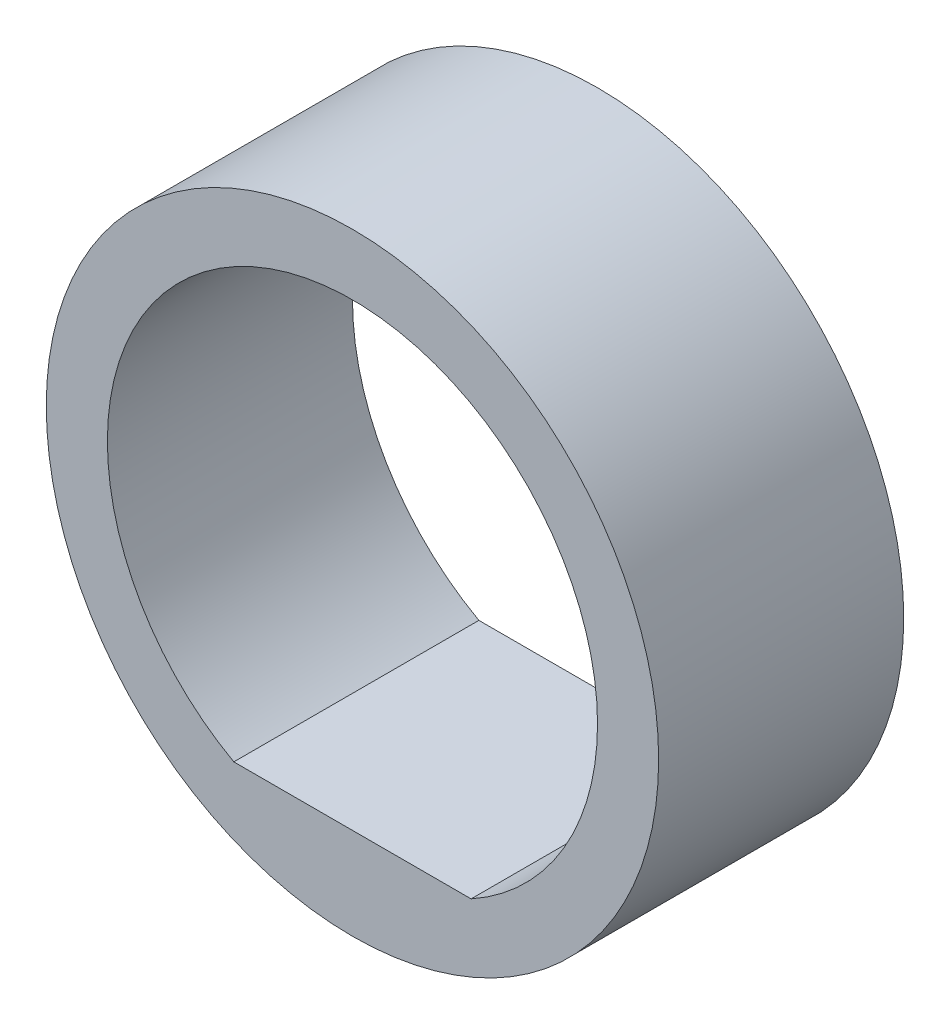
SolidWorks part; units mm, degrees
ref_plane "Front Plane" through (0, 0, 0) normal (0, 0, 1) x (1, 0, 0)
ref_plane "Top Plane" through (0, 0, 0) normal (0, 1, 0) x (1, 0, 0)
ref_plane "Right Plane" through (0, 0, 0) normal (1, 0, 0) x (0, 0, -1)
sketch "Sketch3" plane through (0, 0, 0) normal (0, 0, 1) x (1, 0, 0)
  line L3 (-111.134, -3.5) -> (-113.0705, -3.5)
  line L5 (-111.134, -3.5) -> (-109.1975, -3.5)
  circle A2 centre (-111.134, 0) radius 4.9975
  arc A3 (-109.1975, -3.5) -> (-113.0705, -3.5) centre (-111.134, 0) ccw
  dimension "D1" = 9.995
extrude "Boss-Extrude1" add sketch "Sketch3" along normal blind 4
